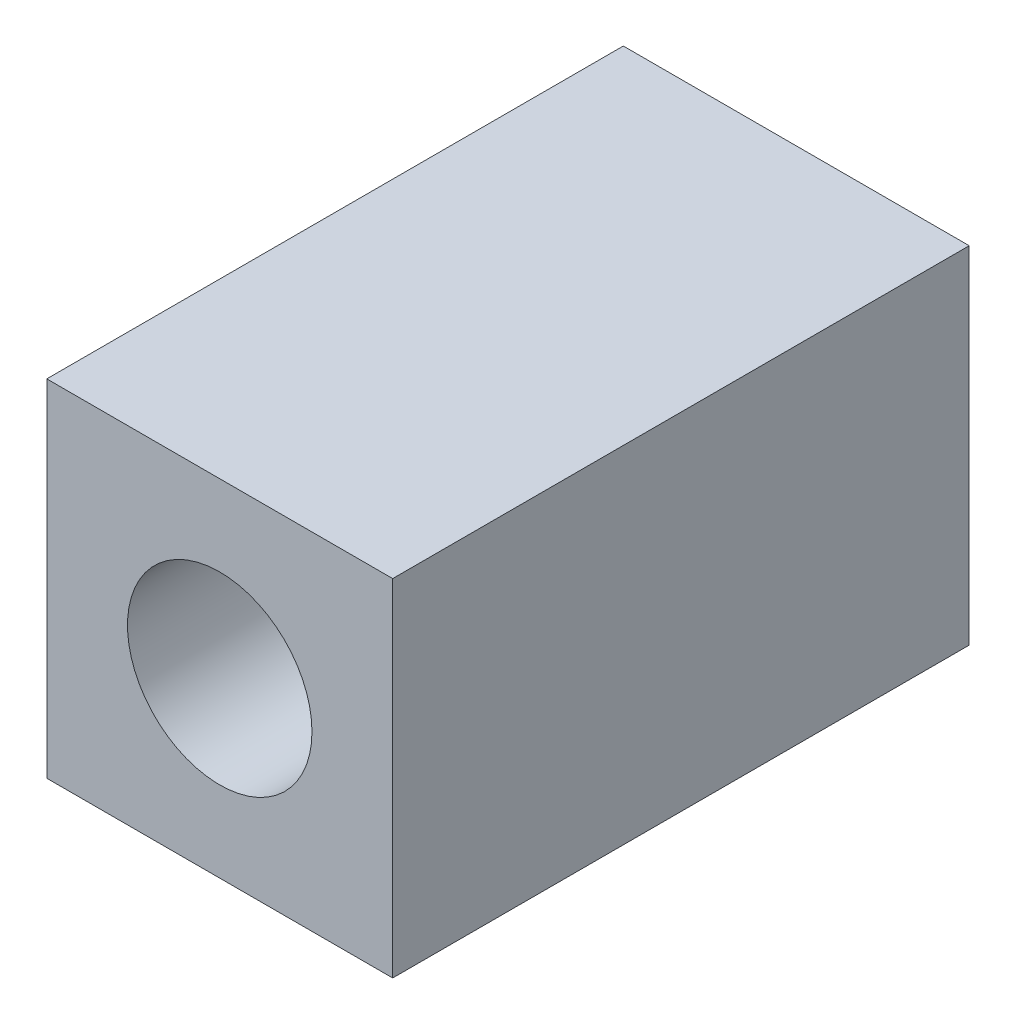
SolidWorks part; units mm, degrees
ref_plane "Спереди" through (0, 0, 0) normal (0, 0, 1) x (1, 0, 0)
ref_plane "Сверху" through (0, 0, 0) normal (0, 1, 0) x (1, 0, 0)
ref_plane "Справа" through (0, 0, 0) normal (1, 0, 0) x (0, 0, -1)
sketch "Эскиз1" plane through (0, 0, 0) normal (0, 0, 1) x (1, 0, 0)
  line L1 (-7.5, -7.5) -> (7.5, -7.5)
  line L2 (-7.5, -7.5) -> (-7.5, 7.5)
  line L3 (-7.5, 7.5) -> (7.5, 7.5)
  line L4 (7.5, -7.5) -> (7.5, 7.5)
  line L5 (-7.5, -7.5) -> (7.5, 7.5) construction
  line L6 (-7.5, 7.5) -> (7.5, -7.5) construction
  point P0 (0, 0)
extrude "Бобышка-Вытянуть1" add sketch "Эскиз1" along normal blind 25 contours L1 L4 L3 L2
sketch "Эскиз2" plane through (0, 0, 25) normal (0, 0, 1) x (1, 0, 0)
  circle A0 centre (0, 0) radius 4
extrude "Вырез-Вытянуть1" cut sketch "Эскиз2" against normal through all
